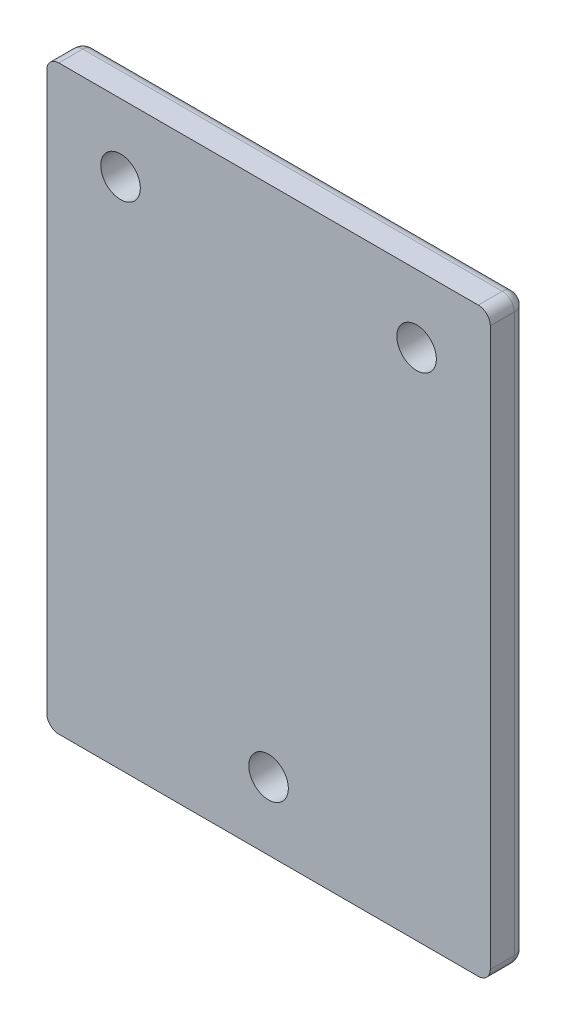
SolidWorks part; units mm, degrees
ref_plane "Front Plane" through (0, 0, 0) normal (0, 0, 1) x (1, 0, 0)
ref_plane "Top Plane" through (0, 0, 0) normal (0, 1, 0) x (1, 0, 0)
ref_plane "Right Plane" through (0, 0, 0) normal (1, 0, 0) x (0, 0, -1)
ref_plane "Plane1" through (0, 0, 0) normal (-0.7071, 0.7071, 0) x (0.7071, 0.7071, 0)
ref_plane "Plane2" through (0, 0, 0) normal (0.7071, 0.7071, 0) x (0.7071, -0.7071, 0)
sketch "Sketch1" plane through (0, 0, 0) normal (0, 0, 1) x (1, 0, 0)
  line L1 (-15.5, -21.25) -> (15.5, -21.25)
  line L2 (-15.5, -21.25) -> (-15.5, 21.25)
  line L3 (-15.5, 21.25) -> (15.5, 21.25)
  line L4 (15.5, -21.25) -> (15.5, 21.25)
  line L5 (-15.5, -21.25) -> (15.5, 21.25) construction
  line L6 (-15.5, 21.25) -> (15.5, -21.25) construction
  point P0 (0, 0)
  dimension "D1" = 31
  dimension "D2" = 42.5
extrude "Boss-Extrude1" add sketch "Sketch1" along normal blind 3
sketch "Sketch2" plane through (0, 0, 0) normal (0, 0, 1) x (1, 0, 0)
  line L0 (-18.5, -24.25) -> (-18.5, 24.25)
  line L1 (-15.5, -21.25) -> (15.5, -21.25)
  line L2 (-15.5, -21.25) -> (-15.5, 21.25)
  line L3 (-15.5, 21.25) -> (15.5, 21.25)
  line L4 (15.5, -21.25) -> (15.5, 21.25)
  line L5 (-15.5, -21.25) -> (15.5, 21.25) construction
  line L6 (-15.5, 21.25) -> (15.5, -21.25) construction
  line L7 (-18.5, 24.25) -> (18.5, 24.25)
  line L8 (18.5, -24.25) -> (18.5, 24.25)
  line L9 (-18.5, -24.25) -> (18.5, -24.25)
  line L10 (15.5, -21.25) -> (15.5, 21.25) construction
  line L11 (-15.5, -21.25) -> (15.5, -21.25) construction
  point P0 (0, 0)
  dimension "D1" = 3
extrude "Boss-Extrude2" add sketch "Sketch2" along normal blind 3
sketch "Sketch3" plane through (0, 0, 0) normal (0, 0, -1) x (-1, 0, 0)
  circle A0 centre (12.35, 18.6) radius 1.65
  circle A1 centre (0, -18.6) radius 1.65
  dimension "D1" = 3.3
  dimension "D2" = 12.35
  dimension "D3" = 18.6
  dimension "D4" = 18.6
extrude "Cut-Extrude1" cut sketch "Sketch3" against normal up to next
mirror "Mirror1" about plane through (0, 0, 0) normal (1, 0, 0) of "Cut-Extrude1"
fillet "Fillet4" radius 1 8 edges at (-18.5, 24.25, 1.5) (-18.5, -24.25, 1.5) (18.5, 24.25, 1.5) (18.5, -24.25, 1.5) (0, 24.25, 0) (-18.5, 0, 0) (0, -24.25, 0) (18.5, 0, 0)
